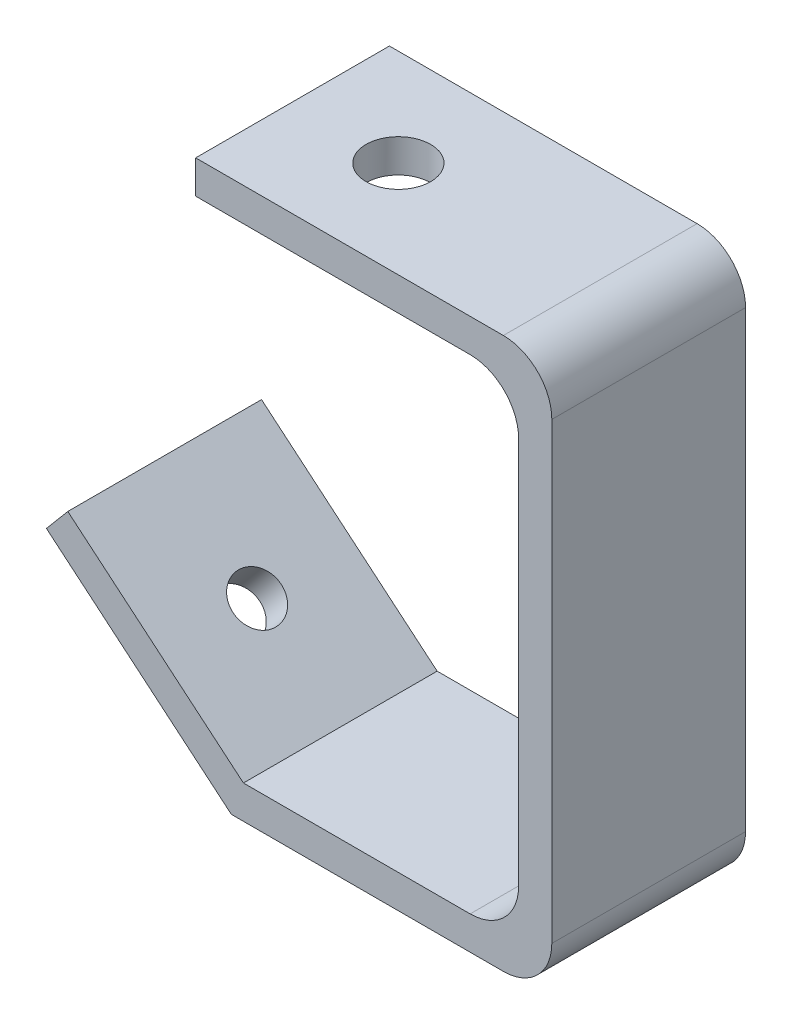
SolidWorks part; units mm, degrees
ref_plane "Front Plane" through (0, 0, 0) normal (0, 0, 1) x (1, 0, 0)
ref_plane "Top Plane" through (0, 0, 0) normal (0, 1, 0) x (1, 0, 0)
ref_plane "Right Plane" through (0, 0, 0) normal (1, 0, 0) x (0, 0, -1)
sketch "Sketch1" plane through (0, 0, 0) normal (0, 0, 1) x (1, 0, 0)
  line L0 (0, 0) -> (0, 31351.8282) construction
  line L1 (0, 0) -> (-31351.8282, 0) construction
  line L2 (0, 0) -> (44.591, 0)
  line L3 (54.121, 9.53) -> (54.121, 85.72)
  line L4 (44.591, 95.25) -> (-9.389, 95.25)
  line L5 (0, 0) -> (-34.5409, 28.9833)
  line L6 (-2.3767, -6.53) -> (-38.7383, 23.981)
  line L7 (-2.3767, -6.53) -> (51.121, -6.53)
  line L8 (60.651, 3) -> (60.651, 92.25)
  line L9 (51.121, 101.78) -> (-9.389, 101.78)
  line L10 (-9.389, 101.78) -> (-9.389, 95.25)
  line L11 (-34.5409, 28.9833) -> (-38.7383, 23.981)
  line L12 (54.121, 0) -> (54.121, 95.25) construction
  line L13 (54.121, 95.25) -> (-9.389, 95.25) construction
  line L14 (60.651, -6.53) -> (60.651, 101.78) construction
  line L15 (60.651, 101.78) -> (-9.389, 101.78) construction
  line L16 (-2.3767, -6.53) -> (60.651, -6.53) construction
  line L17 (0, 0) -> (54.121, 0) construction
  arc A0 (54.121, 85.72) -> (44.591, 95.25) centre (44.591, 85.72) ccw
  arc A1 (60.651, 92.25) -> (51.121, 101.78) centre (51.121, 92.25) ccw
  arc A2 (51.121, -6.53) -> (60.651, 3) centre (51.121, 3) ccw
  arc A3 (44.591, 0) -> (54.121, 9.53) centre (44.591, 9.53) ccw
  point P18 (54.121, 95.25)
  dimension "D7" = 9.53
  dimension "D1" = 63.51
  dimension "D3" = 140
  dimension "D5" = 45.09
  dimension "D6" = 6.53
extrude "Boss-Extrude1" add sketch "Sketch1" along normal blind 38.1
sketch "Sketch2" plane through (0, 101.78, 0) normal (0, 1, 0) x (1, 0, 0)
  line L0 (-9.389, -38.1) -> (-9.389, 0) construction
  line L2 (51.121, -38.1) -> (-9.389, -38.1) construction
  circle A0 centre (11.421, -19.05) radius 6.35
  dimension "D1" = 12.7
  dimension "D2" = 20.81
  dimension "D3" = 19.05
extrude "Cut-Extrude1" cut sketch "Sketch2" against normal blind 86.1
sketch "Sketch4" plane through (-4.1974, -5.0023, 0) normal (-0.6428, -0.766, 0) x (0.766, -0.6428, 0)
  line L0 (-45.09, 38.1) -> (2.3767, 0)
  line L1 (2.3767, 0) -> (2.3767, 38.1)
  line L2 (2.3767, 38.1) -> (-45.09, 0)
  line L3 (-45.09, 0) -> (-45.09, 38.1)
  circle A0 centre (-21.3566, 19.05) radius 4.765
  dimension "D1" = 9.53
extrude "Cut-Extrude2" cut sketch "Sketch4" against normal blind 9.1 contours L2 A0 L0 | L0 A0 L2 | L2 A0 L0 | L0 A0 L2
